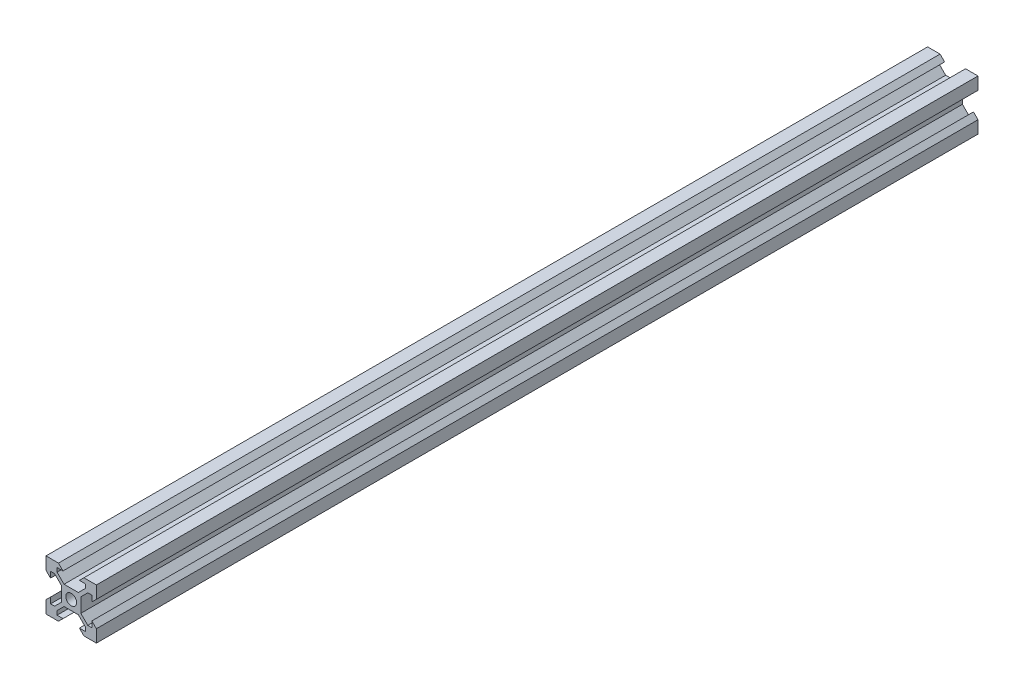
SolidWorks part; units mm, degrees
ref_plane "Alzado" through (0, 0, 0) normal (0, 0, 1) x (1, 0, 0)
ref_plane "Planta" through (0, 0, 0) normal (0, 1, 0) x (1, 0, 0)
ref_plane "Vista lateral" through (0, 0, 0) normal (1, 0, 0) x (0, 0, -1)
sketch "Croquis1" plane through (0, 0, 0) normal (0, 0, 1) x (1, 0, 0)
  line L0 (0, 0) -> (0, -20) construction
  line L2 (0, 0) -> (0, -0.5674)
  line L5 (6.175, -7.1649) -> (6.175, -12.8351)
  line L6 (7.1649, -13.825) -> (12.8351, -13.825)
  line L7 (13.825, -7.1649) -> (13.825, -12.8351)
  line L8 (7.1649, -6.175) -> (12.8351, -6.175)
  line L9 (6.175, -13.825) -> (13.825, -13.825) construction
  line L10 (13.825, -6.175) -> (13.825, -13.825) construction
  line L12 (10, -10) -> (32.1172, -10) construction
  line L13 (13.25, -18.2) -> (15.05, -20)
  line L14 (20, -20) -> (15.6, -20)
  line L15 (20, -20) -> (20, -15.6)
  line L16 (18.2, -15.6) -> (16.5899, -15.6)
  line L32 (15.6, -18.2) -> (15.6, -16.5899)
  line L33 (10, -10) -> (10, -23.2493) construction
  line L34 (4.4, -18.2) -> (4.4, -16.5899)
  line L35 (7.1649, -13.825) -> (4.4, -16.5899)
  line L36 (15.6, -18.2) -> (13.25, -18.2)
  line L38 (15.6, -20) -> (15.05, -20)
  line L40 (15.05, -20) -> (20, -20)
  line L41 (0, -20) -> (20, -20) construction
  line L42 (6.175, -12.8351) -> (3.4101, -15.6)
  line L43 (18.2, -13.25) -> (20, -15.05)
  line L44 (20, -20) -> (18.2, -20)
  line L45 (20, -20) -> (20, -15.05)
  line L48 (20, -15.05) -> (20, -20)
  line L49 (20, 0) -> (20, -20) construction
  line L50 (18.2, -15.6) -> (18.2, -13.25)
  line L51 (12.8351, -13.825) -> (15.6, -16.5899)
  line L52 (13.825, -12.8351) -> (16.5899, -15.6)
  line L53 (1.8, -15.6) -> (3.4101, -15.6)
  line L54 (1.8, -15.6) -> (1.8, -13.25)
  line L55 (1.8, -13.25) -> (0, -15.05)
  line L56 (0, 0) -> (20, 0) construction
  line L57 (0, -20) -> (0, -15.6)
  line L58 (0, -15.6) -> (0, -15.05)
  line L59 (0, -20) -> (4.4, -20)
  line L60 (0, -20) -> (4.95, -20)
  line L61 (6.75, -18.2) -> (4.95, -20)
  line L62 (4.4, -18.2) -> (6.75, -18.2)
  line L63 (1.8, -4.4) -> (3.4101, -4.4)
  line L64 (6.175, -7.1649) -> (3.4101, -4.4)
  line L65 (7.1649, -6.175) -> (4.4, -3.4101)
  line L66 (4.4, -1.8) -> (4.4, -3.4101)
  line L67 (4.4, -1.8) -> (6.75, -1.8)
  line L68 (6.75, -1.8) -> (4.95, 0)
  line L69 (0, 0) -> (4.4, 0)
  line L70 (4.4, 0) -> (4.95, 0)
  line L71 (0, 0) -> (0, -4.4)
  line L72 (0, 0) -> (0, -4.95)
  line L73 (1.8, -6.75) -> (0, -4.95)
  line L74 (1.8, -4.4) -> (1.8, -6.75)
  line L75 (15.6, -1.8) -> (15.6, -3.4101)
  line L76 (12.8351, -6.175) -> (15.6, -3.4101)
  line L77 (13.825, -7.1649) -> (16.5899, -4.4)
  line L78 (18.2, -4.4) -> (16.5899, -4.4)
  line L79 (18.2, -4.4) -> (18.2, -6.75)
  line L80 (18.2, -6.75) -> (20, -4.95)
  line L81 (20, 0) -> (20, -4.4)
  line L82 (20, -4.4) -> (20, -4.95)
  line L83 (20, 0) -> (15.6, 0)
  line L84 (20, 0) -> (15.05, 0)
  line L85 (13.25, -1.8) -> (15.05, 0)
  line L86 (15.6, -1.8) -> (13.25, -1.8)
  line L87 (6.175, -6.175) -> (13.825, -6.175) construction
  line L88 (6.175, -6.175) -> (6.175, -13.825) construction
  circle A0 centre (10, -10) radius 2.15
  point P69 (10, -10)
  dimension "D3" = 4.3
  dimension "D2" = 4
  dimension "D11" = 4.4
  dimension "D15" = 4.4
  dimension "D16" = 6.75
extrude "BoschBase" add sketch "Croquis1" along normal blind 350 contours L86 L75 L76 L8 L65 L66 L67 L68 L70 L69 L2 L71 L72 L73 L74 L63 L64 L5 L42 L53 L54 L55 L58 L57 L59 L60 L61 L62 L34 L35 L6 L51 L32 L36 L13 L38 L40 L14 L15 L45 L43 L50 L16 L52 L7 L77 L78 L79 L80 L82 L81
